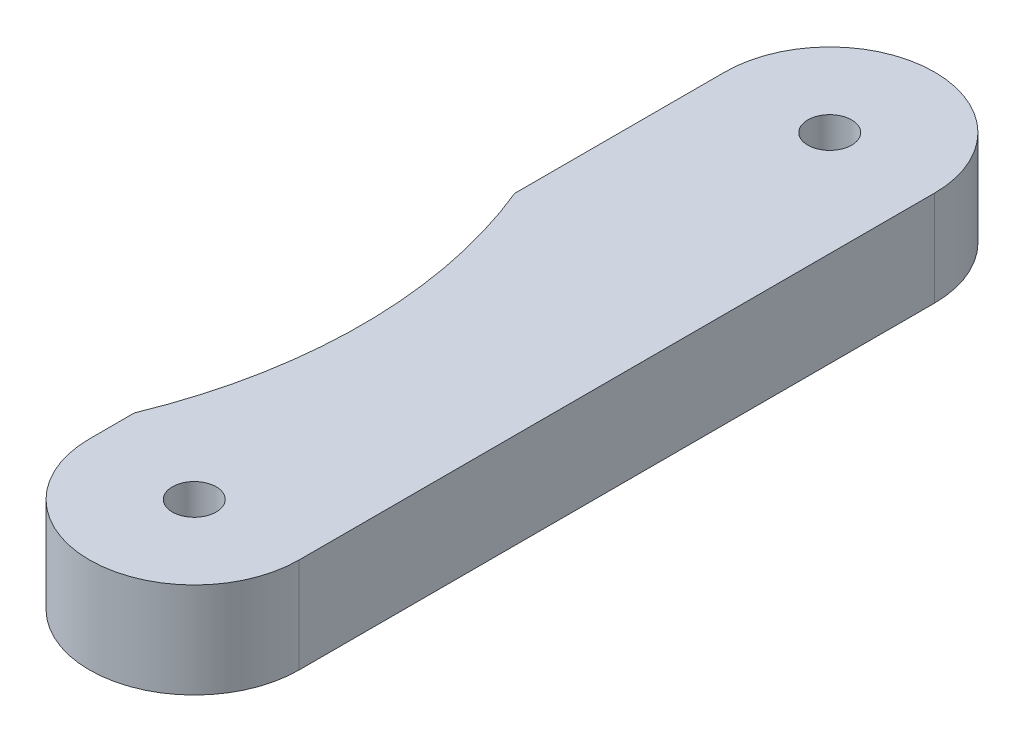
SolidWorks part; units mm, degrees
material "7075-T6, Plate (SS)"
ref_plane "Front Plane" through (0, 0, 0) normal (0, 0, 1) x (1, 0, 0)
ref_plane "Top Plane" through (0, 0, 0) normal (0, 1, 0) x (1, 0, 0)
ref_plane "Right Plane" through (0, 0, 0) normal (1, 0, 0) x (0, 0, -1)
sketch "Sketch1" plane through (0, 0, 0) normal (0, 1, 0) x (1, 0, 0)
  line L0 (0.3077, 6.5172) -> (0.3077, -18.8828)
  line L1 (8.6897, 6.5172) -> (8.6897, -18.8828)
  arc A0 (0.3077, 6.5172) -> (8.6897, 6.5172) centre (4.4987, 6.5172) cw
  arc A1 (8.6897, -18.8828) -> (0.3077, -18.8828) centre (4.4987, -18.8828) cw
  dimension "D1" = 25.4
  dimension "D2" = 8.382
extrude "Boss-Extrude1" add sketch "Sketch1" along normal blind 3.81
hole_wizard "#4-40 Tapped Hole1" positions "Sketch2" profile "Sketch3" tap size "#4-40" standard "ANSI Inch" end condition through all
sketch "Sketch2" plane through (0, 3.81, 0) normal (0, 1, 0) x (1, 0, 0)
  arc A0 (0.3077, -18.8828) -> (8.6897, -18.8828) centre (4.4987, -18.8828) ccw construction
  arc A1 (8.6897, 6.5172) -> (0.3077, 6.5172) centre (4.4987, 6.5172) ccw construction
  point P0 (4.4987, 6.5172)
  point P2 (4.4987, -18.8828)
sketch "Sketch3" plane through (4.4987, 3.81, -6.5172) normal (1, 0, 0) x (0, 0, 1)
  line L0 (0, 0) -> (0, 3.81)
  line L1 (0, 3.81) -> (0.8763, 3.81)
  line L2 (0.8763, 3.81) -> (0.8763, 0)
  line L5 (0.8763, 0) -> (0, 0)
  line L11 (0, -6.35) -> (0, 107.95) construction
  dimension "Thru Tap Drill Dia." = 1.7526
  dimension "Thru Tap Drill Depth" = 3.81
cosmetic thread "Hole Thread1" parameters "D2"=2.8448
cosmetic thread "Hole Thread2" parameters "D2"=2.8448
sketch "Sketch4" plane through (0, 3.81, 0) normal (0, 1, 0) x (1, 0, 0)
  line L0 (0.3077, -9.4848) -> (-18.1923, -9.4848) construction
  line L1 (0.3077, 6.5172) -> (0.3077, -18.8828) construction
  line L2 (0.3077, -17.0841) -> (0.3077, -1.8854)
  arc A0 (0.3077, -17.0841) -> (0.3077, -1.8854) centre (-18.1923, -9.4848) ccw
  circle A1 centre (4.4987, -18.8828) radius 0.8763 construction
  dimension "D1" = 20
  dimension "D2" = 9.398
  dimension "D3" = 18.5
extrude "Cut-Extrude1" cut sketch "Sketch4" against normal through all
